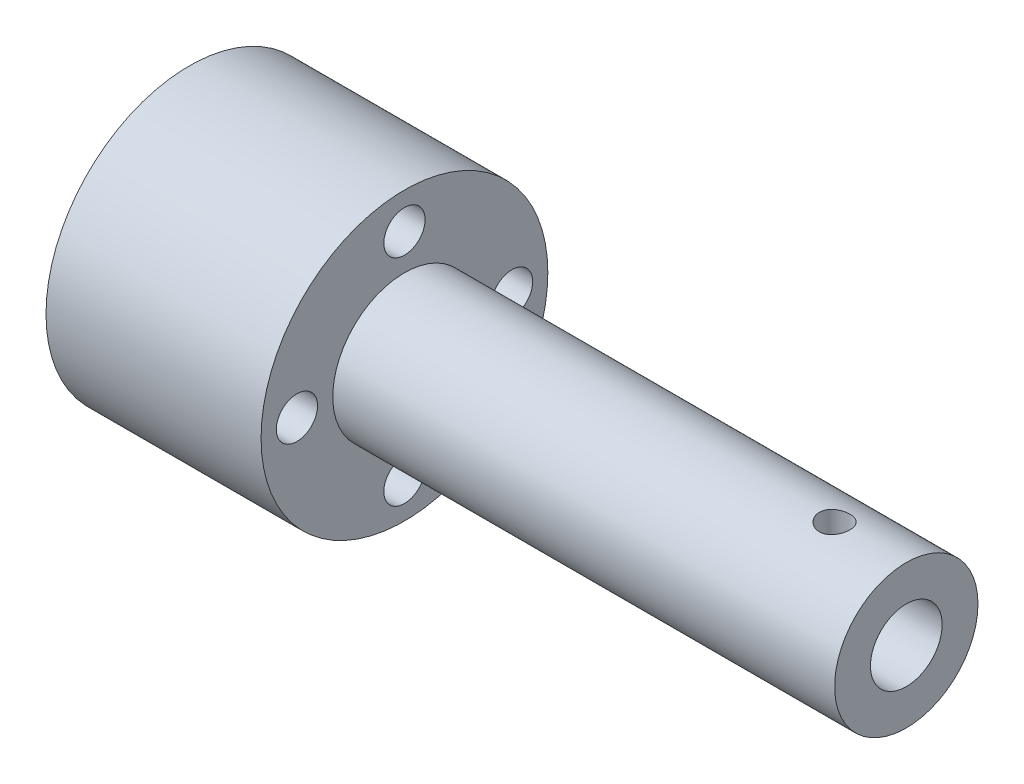
SolidWorks part; units mm, degrees
ref_plane "Front Plane" through (0, 0, 0) normal (0, 0, 1) x (1, 0, 0)
ref_plane "Top Plane" through (0, 0, 0) normal (0, 1, 0) x (1, 0, 0)
ref_plane "Right Plane" through (0, 0, 0) normal (1, 0, 0) x (0, 0, -1)
sketch "Sketch1" plane through (0, 0, 0) normal (1, 0, 0) x (0, 0, -1)
  circle A0 centre (0, 0) radius 12.7
  dimension "D1" = 25.4
extrude "Boss-Extrude1" add sketch "Sketch1" along normal mid plane 63.5
sketch "Sketch2" plane through (31.75, 0, 0) normal (1, 0, 0) x (0, 0, -1)
  circle A0 centre (0, 0) radius 3.175
  dimension "D1" = 6.35
extrude "Cut-Extrude1" cut sketch "Sketch2" against normal blind 15.875
sketch "Sketch3" plane through (31.75, 0, 0) normal (1, 0, 0) x (0, 0, -1)
  circle A0 centre (0, 0) radius 6.35
  circle A1 centre (0, 0) radius 12.7 construction
  circle A2 centre (0, 0) radius 12.7
  dimension "D1" = 12.7
extrude "Cut-Extrude2" cut sketch "Sketch3" against normal blind 44.45
sketch "Sketch4" plane through (-12.7, 0, 0) normal (1, 0, 0) x (0, 0, -1)
  circle A0 centre (9.525, 0) radius 1.8288
  point P0 (9.525, 0)
  dimension "D2" = 3.6576
  dimension "D1" = 9.525
sketch "Sketch7" plane through (0, 0, 0) normal (0, 1, 0) x (1, 0, 0)
  line L1 (31.75, -6.35) -> (31.75, 6.35) construction
  point P6 (25.4, 0)
  dimension "D1" = 6.35
hole_wizard "#6-32 Tapped Hole2" positions "Sketch9" profile "Sketch8" tap size "#6-32" standard "ANSI Inch"
sketch "Sketch9" plane through (0, 0, 0) normal (0, 1, 0) x (1, 0, 0)
  point P0 (25.4, 0)
sketch "Sketch8" plane through (25.4, 0, 0) normal (1, 0, 0) x (0, 0, -1)
  line L0 (0, 0) -> (0, 12.7)
  line L1 (0, 12.7) -> (1.3525, 12.7)
  line L2 (1.3525, 12.7) -> (1.3525, 0)
  line L5 (1.3525, 0) -> (0, 0)
  line L11 (0, -6.35) -> (0, 107.95) construction
  dimension "Thru Tap Drill Dia." = 2.7051
  dimension "Thru Tap Drill Depth" = 12.7
cosmetic thread "Hole Thread2" parameters "D2"=3.5052
extrude "Cut-Extrude3" cut sketch "Sketch4" against normal through all
sketch "Sketch10" plane through (-31.75, 0, 0) normal (-1, 0, 0) x (0, 0, 1)
  circle A0 centre (-9.525, 0) radius 2.921
  dimension "D1" = 5.842
extrude "Cut-Extrude5" cut sketch "Sketch10" against normal blind 9.525
pattern_circular "CirPattern1" count 4 over 360 about axis through (0, 0, 0) along (1, 0, 0) of "Cut-Extrude5", "Cut-Extrude3"
